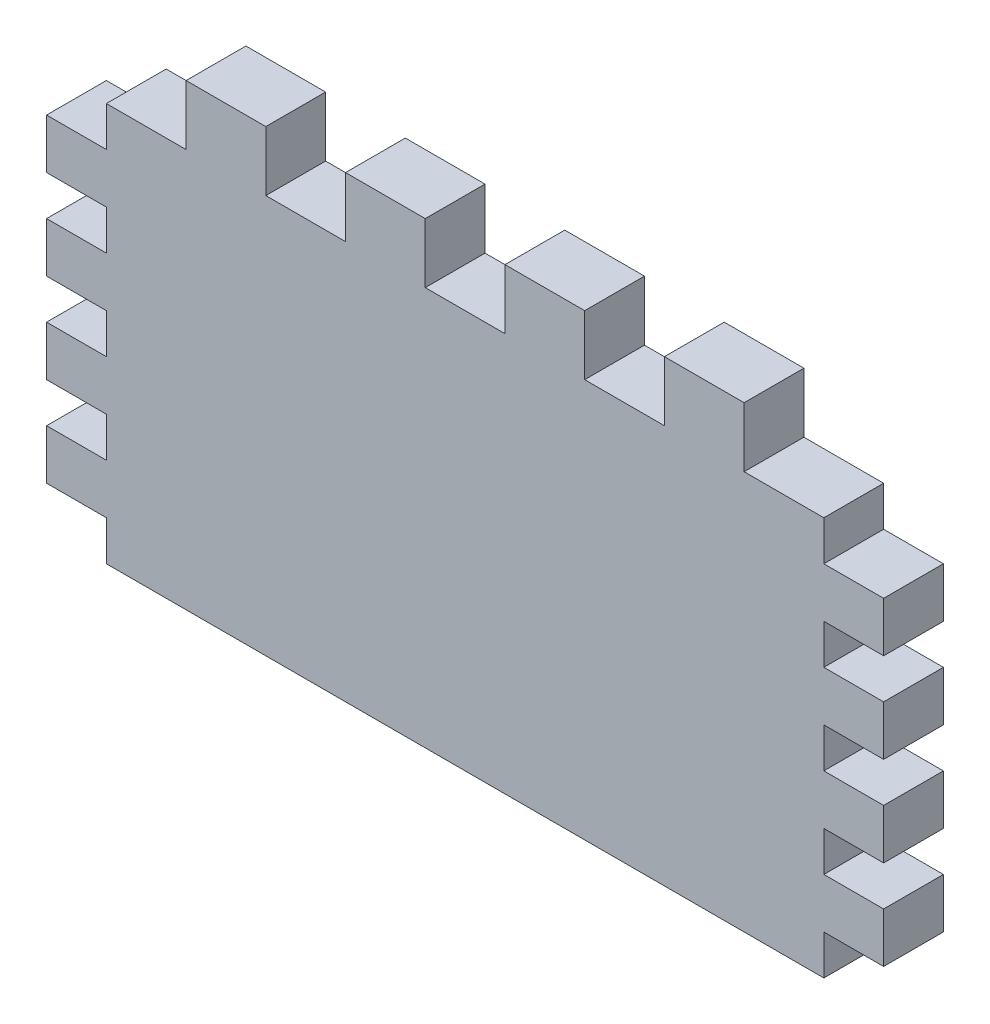
SolidWorks part; units mm, degrees
ref_plane "Front Plane" through (0, 0, 0) normal (0, 0, 1) x (1, 0, 0)
ref_plane "Top Plane" through (0, 0, 0) normal (0, 1, 0) x (1, 0, 0)
ref_plane "Right Plane" through (0, 0, 0) normal (1, 0, 0) x (0, 0, -1)
sketch "Sketch1" plane through (0, 0, 0) normal (0, 0, 1) x (1, 0, 0)
  line L0 (18, 10) -> (18, 8)
  line L1 (18, 8) -> (21, 8)
  line L2 (21, 8) -> (21, 5.5)
  line L3 (21, 5.5) -> (18, 5.5)
  line L4 (18, 5.5) -> (18, 3.5)
  line L5 (18, 3.5) -> (21, 3.5)
  line L6 (21, 3.5) -> (21, 1)
  line L7 (21, 1) -> (18, 1)
  line L8 (18, 1) -> (18, -1)
  line L9 (18, -1) -> (21, -1)
  line L10 (21, -1) -> (21, -3.5)
  line L11 (21, -3.5) -> (18, -3.5)
  line L12 (18, -3.5) -> (18, -5.5)
  line L13 (18, -5.5) -> (21, -5.5)
  line L14 (21, -5.5) -> (21, -8)
  line L15 (21, -8) -> (18, -8)
  line L16 (18, -8) -> (18, -10)
  line L17 (18, -10) -> (-18, -10)
  line L18 (0, 0) -> (0, 10) construction
  line L19 (-18, 10) -> (-14, 10)
  line L20 (-14, 10) -> (-14, 13)
  line L21 (-14, 13) -> (-10, 13)
  line L22 (-10, 13) -> (-10, 10)
  line L23 (-6, 10) -> (-6, 13)
  line L24 (-6, 13) -> (-2, 13)
  line L25 (-2, 13) -> (-2, 10)
  line L26 (2, 10) -> (2, 13)
  line L27 (2, 13) -> (6, 13)
  line L28 (6, 13) -> (6, 10)
  line L29 (10, 10) -> (10, 13)
  line L30 (10, 13) -> (14, 13)
  line L31 (14, 13) -> (14, 10)
  line L32 (-10, 10) -> (-6, 10)
  line L33 (-2, 10) -> (2, 10)
  line L34 (6, 10) -> (10, 10)
  line L35 (14, 10) -> (18, 10)
  line L41 (-18, -8) -> (-18, -10)
  line L42 (-21, -8) -> (-18, -8)
  line L43 (-21, -5.5) -> (-21, -8)
  line L44 (-18, -5.5) -> (-21, -5.5)
  line L45 (-18, -3.5) -> (-18, -5.5)
  line L46 (-21, -3.5) -> (-18, -3.5)
  line L47 (-21, -1) -> (-21, -3.5)
  line L48 (-18, -1) -> (-21, -1)
  line L49 (-18, 1) -> (-18, -1)
  line L50 (-21, 1) -> (-18, 1)
  line L51 (-21, 3.5) -> (-21, 1)
  line L52 (-18, 3.5) -> (-21, 3.5)
  line L53 (-18, 5.5) -> (-18, 3.5)
  line L54 (-21, 5.5) -> (-18, 5.5)
  line L55 (-21, 8) -> (-21, 5.5)
  line L56 (-18, 8) -> (-21, 8)
  line L57 (-18, 10) -> (-18, 8)
  point P36 (-18, 0)
  point P37 (0, -10)
  dimension "D1" = 2
  dimension "D2" = 20
  dimension "D5" = 3
  dimension "D6" = 3
extrude "Boss-Extrude1" add sketch "Sketch1" along normal blind 3
